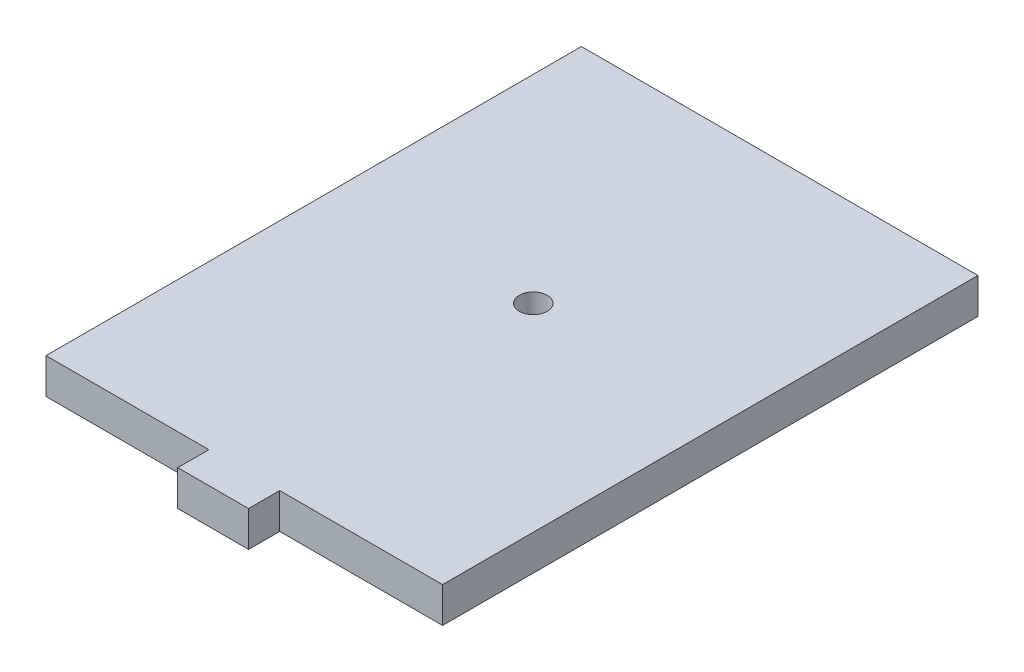
SolidWorks part; units mm, degrees
ref_plane "Front Plane" through (0, 0, 0) normal (0, 0, 1) x (1, 0, 0)
ref_plane "Top Plane" through (0, 0, 0) normal (0, 1, 0) x (1, 0, 0)
ref_plane "Right Plane" through (0, 0, 0) normal (1, 0, 0) x (0, 0, -1)
sketch "Sketch1" plane through (0, 0, 0) normal (0, 0, 1) x (1, 0, 0)
  line L0 (0, 0) -> (35.56, 0)
  line L1 (35.56, 0) -> (35.56, 3.175)
  line L2 (35.56, 3.175) -> (0, 3.175)
  line L3 (0, 3.175) -> (0, 0)
  point P2 (0, 30.6407)
  point P4 (4.9657, 5.3446)
  dimension "D1" = 35.56
  dimension "D2" = 3.175
extrude "Boss-Extrude1" add sketch "Sketch1" along normal blind 50.8
sketch "Sketch2" plane through (0, 3.175, 0) normal (0, 1, 0) x (1, 0, 0)
  line L0 (0, 0) -> (0, -50.8) construction
  line L1 (35.56, -22.098) -> (0, -22.098) construction
  line L4 (35.56, -50.8) -> (0, -50.8) construction
  line L5 (35.56, -50.8) -> (35.56, 0) construction
  circle A0 centre (17.78, -22.098) radius 1.25
  point P10 (18.5686, -34.29)
  point P11 (0, 0)
  point P14 (18.6625, -34.29)
  point P15 (0, 0)
  dimension "D1" = 2.5
  dimension "D2" = 28.702
extrude "Cut-Extrude1" cut sketch "Sketch2" against normal through all
sketch "Sketch3" plane through (0, 3.175, 0) normal (0, 1, 0) x (1, 0, 0)
  line L1 (0, -50.8) -> (14.605, -50.8)
  line L2 (0, -50.8) -> (0, -48.006)
  line L3 (0, -48.006) -> (14.605, -48.006)
  line L4 (14.605, -50.8) -> (14.605, -48.006)
  line L5 (35.56, -50.8) -> (20.955, -50.8)
  line L6 (35.56, -50.8) -> (35.56, -48.006)
  line L7 (35.56, -48.006) -> (20.955, -48.006)
  line L8 (20.955, -50.8) -> (20.955, -48.006)
  dimension "D1" = 6.35
  dimension "D2" = 2.794
extrude "Cut-Extrude2" cut sketch "Sketch3" against normal through all
